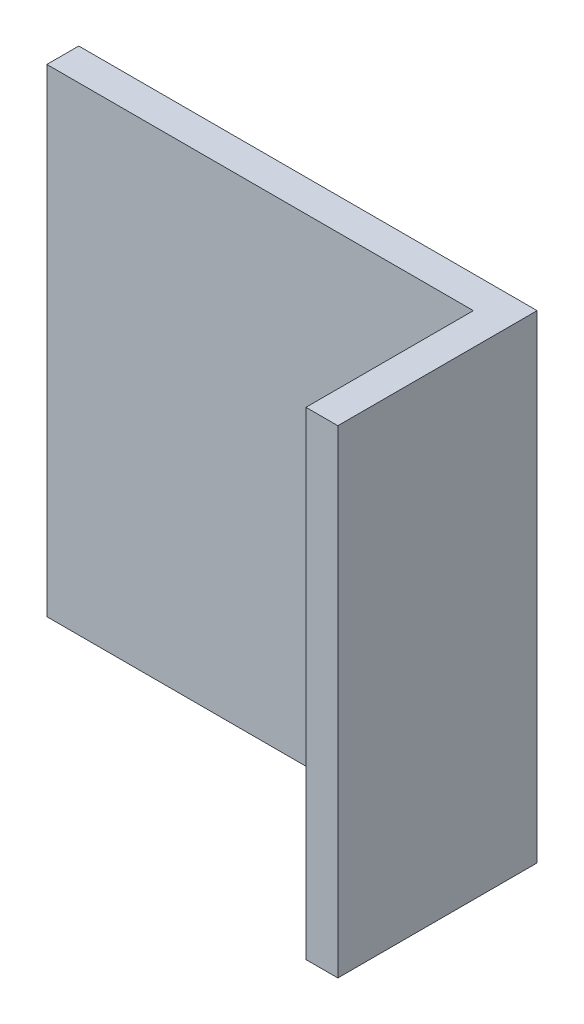
SolidWorks part; units mm, degrees
ref_plane "前视基准面" through (0, 0, 0) normal (0, 0, 1) x (1, 0, 0)
ref_plane "上视基准面" through (0, 0, 0) normal (0, 1, 0) x (1, 0, 0)
ref_plane "右视基准面" through (0, 0, 0) normal (1, 0, 0) x (0, 0, -1)
sketch "草图1" plane through (0, 0, 0) normal (0, 0, 1) x (1, 0, 0)
  line L1 (115, -120) -> (-115, -120)
  line L2 (115, -120) -> (115, 120)
  line L3 (115, 120) -> (-115, 120)
  line L4 (-115, -120) -> (-115, 120)
  line L5 (115, -120) -> (-115, 120) construction
  line L6 (115, 120) -> (-115, -120) construction
  point P0 (0, 0)
extrude "凸台-拉伸1" add sketch "草图1" along normal blind 16
sketch "草图2" plane through (0, 0, 16) normal (0, 0, 1) x (1, 0, 0)
  line L0 (-115, 80) -> (115, 80) construction
  line L1 (-115, 120) -> (-115, -120) construction
  line L2 (115, -120) -> (115, 120) construction
  line L3 (115, 120) -> (-115, 120) construction
  line L4 (43.5, 120) -> (43.5, -120) construction
  line L5 (-115, -120) -> (115, -120) construction
  line L6 (-14.5, 120) -> (-14.5, -120) construction
  line L7 (-73, 120) -> (-73, -120) construction
  dimension "D1" = 40
  dimension "D2" = 71.5
  dimension "D3" = 58
  dimension "D4" = 58.5
sketch "草图3" plane through (0, 0, 16) normal (0, 0, 1) x (1, 0, 0)
  line L0 (-115, 80) -> (115, 80) construction
  line L1 (-73, 120) -> (-73, -120) construction
  line L2 (-14.5, 120) -> (-14.5, -120) construction
  line L3 (43.5, 120) -> (43.5, -120) construction
  circle A0 centre (-73, 80) radius 13
  circle A1 centre (-14.5, 80) radius 13
  circle A2 centre (43.5, 80) radius 13
extrude "切除-拉伸1" cut sketch "草图3" against normal through all
pattern_linear "阵列(线性)1" count 3 spacing 80 along (0, -1, 0) of "切除-拉伸1"
sketch "草图4" plane through (0, 0, 16) normal (0, 0, 1) x (1, 0, 0)
  line L1 (115, -120) -> (99, -120)
  line L2 (115, -120) -> (115, 120)
  line L3 (115, 120) -> (99, 120)
  line L4 (99, -120) -> (99, 120)
extrude "凸台-拉伸2" add sketch "草图4" along normal blind 84
sketch "草图5" plane through (99, 0, 0) normal (-1, 0, 0) x (0, 0, 1)
  line L0 (16, 80) -> (100, 80) construction
  line L1 (16, 120) -> (16, -120) construction
  line L2 (100, 120) -> (100, -120) construction
  line L3 (100, 120) -> (16, 120) construction
  line L4 (48, 120) -> (48, -120) construction
  line L5 (100, -120) -> (16, -120) construction
  circle A0 centre (48, 80) radius 13
  dimension "D1" = 40
  dimension "D2" = 52
extrude "切除-拉伸2" cut sketch "草图5" against normal through all
pattern_linear "阵列(线性)2" count 3 spacing 80 along (0, -1, 0) of "切除-拉伸2"
sketch "草图6" plane through (0, 0, 16) normal (0, 0, 1) x (1, 0, 0)
  line L1 (-115, 120) -> (99, 120)
  line L2 (-115, 120) -> (-115, -120)
  line L3 (-115, -120) -> (99, -120)
  line L4 (99, 120) -> (99, -120)
extrude "凸台-拉伸3" add sketch "草图6" against normal blind 16
sketch "草图7" plane through (99, 0, 0) normal (-1, 0, 0) x (0, 0, 1)
  line L1 (16, 120) -> (100, 120)
  line L2 (16, 120) -> (16, -120)
  line L3 (16, -120) -> (100, -120)
  line L4 (100, 120) -> (100, -120)
extrude "凸台-拉伸4" add sketch "草图7" against normal blind 16
